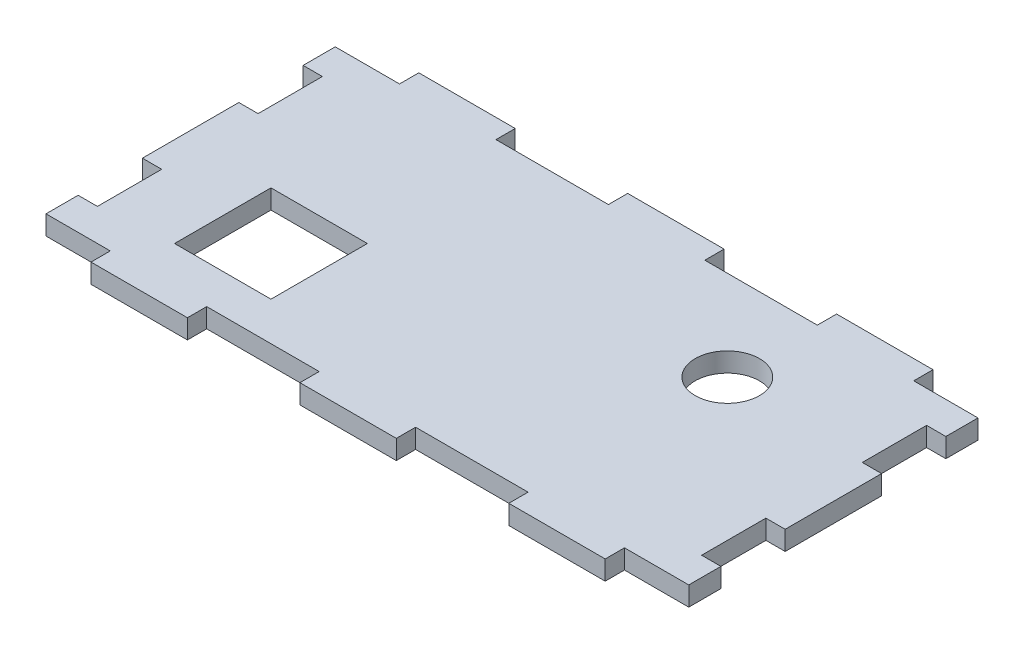
SolidWorks part; units mm, degrees
ref_plane "前视基准面" through (0, 0, 0) normal (0, 0, 1) x (1, 0, 0)
ref_plane "上视基准面" through (0, 0, 0) normal (0, 1, 0) x (1, 0, 0)
ref_plane "右视基准面" through (0, 0, 0) normal (1, 0, 0) x (0, 0, -1)
sketch "草图1" plane through (0, 0, 0) normal (0, 1, 0) x (1, 0, 0)
  line L0 (0, -22.5) -> (0, 22.5) construction
  line L1 (-50, -22.5) -> (-40, -22.5)
  line L2 (-50, -22.5) -> (-50, -17.5)
  line L3 (-50, 22.5) -> (-40, 22.5)
  line L4 (50, -22.5) -> (50, -17.5)
  line L5 (-50, -22.5) -> (50, 22.5) construction
  line L6 (-50, 22.5) -> (50, -22.5) construction
  line L7 (-50, 17.5) -> (-47, 17.5)
  line L8 (-50, -7.5) -> (-50, 7.5)
  line L9 (-50, 7.5) -> (-47, 7.5)
  line L10 (-47, 17.5) -> (-47, 7.5)
  line L11 (-50, 0) -> (50, 0) construction
  line L12 (-50, -7.5) -> (-47, -7.5)
  line L13 (-50, -17.5) -> (-47, -17.5)
  line L14 (-47, -17.5) -> (-47, -7.5)
  line L15 (-50, 17.5) -> (-50, 22.5)
  line L16 (50, -17.5) -> (47, -17.5)
  line L17 (47, -17.5) -> (47, -7.5)
  line L18 (50, -7.5) -> (47, -7.5)
  line L19 (50, 7.5) -> (47, 7.5)
  line L20 (47, 17.5) -> (47, 7.5)
  line L21 (50, 17.5) -> (47, 17.5)
  line L22 (50, 17.5) -> (50, 22.5)
  line L23 (50, -7.5) -> (50, 7.5)
  line L24 (-25, 22.5) -> (-7.5, 22.5)
  line L25 (7.5, 22.5) -> (25, 22.5)
  line L26 (-40, 22.5) -> (-40, 25.5)
  line L27 (-40, 25.5) -> (-25, 25.5)
  line L28 (-25, 22.5) -> (-25, 25.5)
  line L29 (40, 22.5) -> (40, 25.5)
  line L30 (-7.5, 22.5) -> (-7.5, 25.5)
  line L31 (-7.5, 25.5) -> (7.5, 25.5)
  line L32 (7.5, 22.5) -> (7.5, 25.5)
  line L33 (25, 22.5) -> (25, 25.5)
  line L34 (40, 25.5) -> (25, 25.5)
  line L35 (40, 22.5) -> (50, 22.5)
  line L36 (40, -22.5) -> (40, -25.5)
  line L37 (40, -25.5) -> (25, -25.5)
  line L38 (25, -22.5) -> (25, -25.5)
  line L39 (7.5, -22.5) -> (7.5, -25.5)
  line L40 (-7.5, -25.5) -> (7.5, -25.5)
  line L41 (-7.5, -22.5) -> (-7.5, -25.5)
  line L42 (-25, -22.5) -> (-25, -25.5)
  line L43 (-40, -25.5) -> (-25, -25.5)
  line L44 (-40, -22.5) -> (-40, -25.5)
  line L45 (-25, -22.5) -> (-7.5, -22.5)
  line L46 (7.5, -22.5) -> (25, -22.5)
  line L47 (40, -22.5) -> (50, -22.5)
  point P0 (0, 0)
  point P13 (0, 0)
  point P16 (0, 0)
  point P36 (0, 25.5)
  dimension "D1" = 45
  dimension "D2" = 100
  dimension "D3" = 3
  dimension "D4" = 10
  dimension "D5" = 5
  dimension "D6" = 15
  dimension "D7" = 3
  dimension "D8" = 15
  dimension "D9" = 3
  dimension "D10" = 10
extrude "凸台-拉伸1" add sketch "草图1" along normal blind 3
sketch "草图2" plane through (0, 3, 0) normal (0, 1, 0) x (1, 0, 0)
  line L0 (-25, -22.5) -> (-7.5, -22.5) construction
  line L1 (-36, -1.5) -> (-21, -1.5)
  line L2 (-36, -1.5) -> (-36, -16.5)
  line L3 (-36, -16.5) -> (-21, -16.5)
  line L4 (-21, -1.5) -> (-21, -16.5)
  line L5 (-50, 7.5) -> (-50, -7.5) construction
  line L6 (50, -7.5) -> (50, 7.5) construction
  circle A0 centre (25, 8.5) radius 5
  dimension "D5" = 10
  dimension "D6" = 25
  dimension "D7" = 10
  dimension "D1" = 6
  dimension "D2" = 14
  dimension "D3" = 15
  dimension "D4" = 15
extrude "切除-拉伸1" cut sketch "草图2" against normal through all
